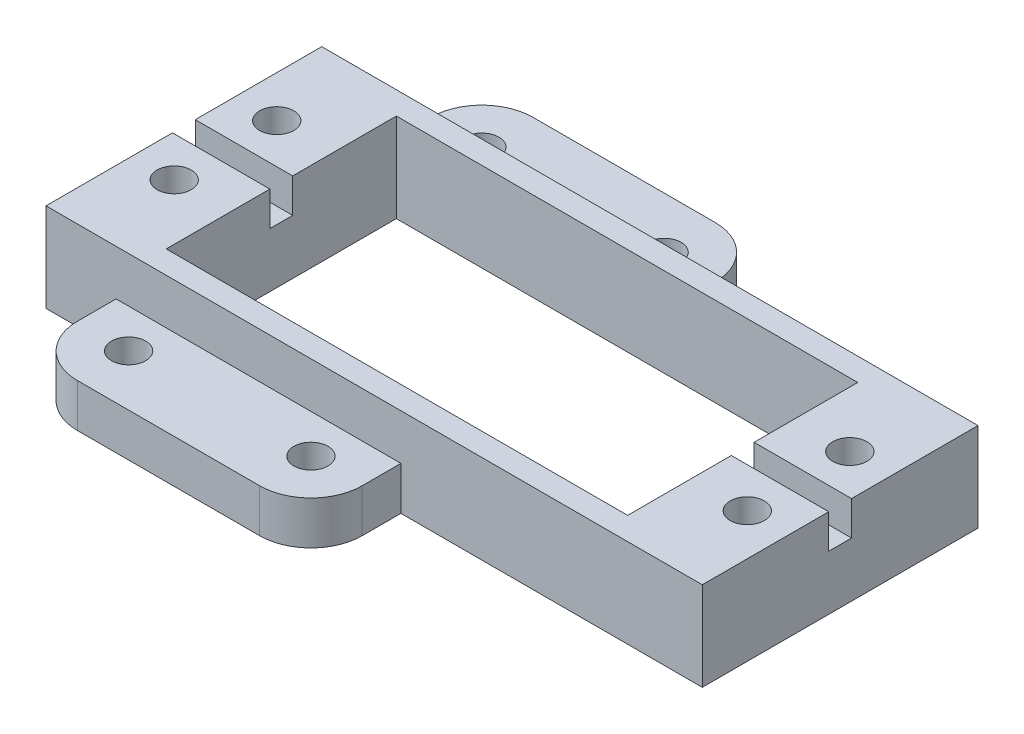
SolidWorks part; units mm, degrees
ref_plane "Front Plane" through (0, 0, 0) normal (0, 0, 1) x (1, 0, 0)
ref_plane "Top Plane" through (0, 0, 0) normal (0, 1, 0) x (1, 0, 0)
ref_plane "Right Plane" through (0, 0, 0) normal (1, 0, 0) x (0, 0, -1)
sketch "Sketch1" plane through (0, 0, 0) normal (0, 1, 0) x (1, 0, 0)
  line L0 (-101.8128, 12.4518) -> (-101.8128, 18.4813)
  line L1 (-101.8128, 21.4518) -> (-101.8128, 24.8665)
  line L2 (-94.5628, 5.4665) -> (-101.2128, 5.4665)
  line L3 (-95.1628, 6.0665) -> (-95.1628, 14.7945)
  line L4 (-54.8628, 14.7945) -> (-54.8628, 6.0665)
  line L5 (-48.2128, 18.4813) -> (-48.2128, 12.4518)
  line L6 (-85.1628, 25.4665) -> (-61.0205, 25.4665)
  line L7 (-95.2628, 25.4665) -> (-95.2628, 5.4665)
  line L8 (-101.8128, 25.4665) -> (-48.2128, 25.4665)
  line L9 (-101.8128, 25.4665) -> (-101.8128, 5.4665)
  line L10 (-101.8128, 5.4665) -> (-48.2128, 5.4665)
  line L11 (-48.2128, 25.4665) -> (-48.2128, 5.4665)
  line L12 (-95.1628, 25.4665) -> (-54.8628, 25.4665)
  line L13 (-95.1628, 25.4665) -> (-95.1628, 5.4665)
  line L14 (-95.1628, 5.4665) -> (-54.8628, 5.4665)
  line L15 (-54.8628, 25.4665) -> (-54.8628, 5.4665)
  line L17 (-54.7628, 25.4665) -> (-54.7628, 5.4665)
  line L19 (-95.2628, 25.5665) -> (-54.7628, 25.5665) construction
  line L20 (-95.2628, 5.3665) -> (-54.7628, 5.3665) construction
  line L22 (-95.2628, 25.5665) -> (-95.2628, 5.3665) construction
  line L23 (-54.7628, 25.5665) -> (-54.7628, 5.3665) construction
  circle A4 centre (-100.1628, 19.9665) radius 1.5
  circle A5 centre (-100.1628, 10.9665) radius 1.5
  circle A6 centre (-49.8628, 19.9665) radius 1.5
  circle A7 centre (-49.8628, 10.9665) radius 1.5
  dimension "D1" = 0.1
extrude "Boss-Extrude1" add sketch "Sketch1" along normal blind 7.8 contours L8 L17 L10 L11 L5 A7 A6 | L9 L10 L2 L7 L8 L1 L0 A5 A4
sketch "Sketch2" plane through (0, 7.8, 0) normal (0, 1, 0) x (1, 0, 0)
  line L5 (-101.8128, 25.4665) -> (-103.8128, 25.4665)
  line L6 (-101.8128, 25.4665) -> (-101.8128, 5.4665)
  line L7 (-101.8128, 5.4665) -> (-103.8128, 5.4665)
  line L8 (-101.8128, 25.4665) -> (-101.8128, 5.4665)
  line L9 (-101.8128, 5.4665) -> (-95.2628, 5.4665)
  line L10 (-95.2628, 5.4665) -> (-95.2628, 25.4665)
  line L11 (-95.2628, 25.4665) -> (-101.8128, 25.4665)
  line L12 (-101.8128, 25.4665) -> (-101.8128, 5.4665)
  line L13 (-101.8128, 5.4665) -> (-95.2628, 5.4665)
  line L14 (-95.2628, 5.4665) -> (-95.2628, 25.4665)
  line L15 (-95.2628, 25.4665) -> (-101.8128, 25.4665)
  line L16 (-103.8128, 25.4665) -> (-103.8128, 5.4665)
  line L17 (-48.2128, 25.4665) -> (-46.2128, 25.4665)
  line L18 (-48.2128, 25.4665) -> (-48.2128, 5.4665)
  line L19 (-48.2128, 5.4665) -> (-46.2128, 5.4665)
  line L20 (-46.2128, 25.4665) -> (-46.2128, 5.4665)
  line M11 (-48.2128, 5.4665) -> (-48.2128, 25.4665)
  dimension "D1" = 0
extrude "Boss-Extrude2" add sketch "Sketch2" against normal blind 7.8 contours L20 L17 L19 M11 | L5 L16 L7 L6
sketch "Sketch3" plane through (0, 7.8, 0) normal (0, 1, 0) x (1, 0, 0)
  line L0 (-54.7628, 25.4665) -> (-46.2128, 25.4665) construction
  line L1 (-95.2628, 25.4665) -> (-54.7628, 25.4665)
  line L2 (-95.2628, 25.4665) -> (-95.2628, 25.5665)
  line L3 (-95.2628, 25.5665) -> (-54.7628, 25.5665)
  line L4 (-54.7628, 25.4665) -> (-54.7628, 25.5665)
  line L5 (-95.2628, 5.4665) -> (-54.7628, 5.4665)
  line L6 (-95.2628, 5.4665) -> (-95.2628, 5.3665)
  line L7 (-95.2628, 5.3665) -> (-54.7628, 5.3665)
  line L8 (-54.7628, 5.4665) -> (-54.7628, 5.3665)
  line L9 (-103.8128, 25.4665) -> (-95.2628, 25.4665)
  line L10 (-103.8128, 25.4665) -> (-103.8128, 25.5665)
  line L11 (-103.8128, 25.5665) -> (-95.2628, 25.5665)
  line L12 (-95.2628, 25.4665) -> (-95.2628, 25.5665)
  line L13 (-54.7628, 25.5665) -> (-46.2128, 25.5665)
  line L14 (-54.7628, 25.5665) -> (-54.7628, 25.4665)
  line L15 (-54.7628, 25.4665) -> (-46.2128, 25.4665)
  line L16 (-46.2128, 25.5665) -> (-46.2128, 25.4665)
  line L17 (-103.8128, 5.4665) -> (-95.2628, 5.4665) construction
  line L18 (-103.8128, 5.4665) -> (-46.2128, 5.4665)
  line L19 (-103.8128, 5.4665) -> (-103.8128, 5.3665)
  line L20 (-103.8128, 5.3665) -> (-46.2128, 5.3665)
  line L21 (-46.2128, 5.4665) -> (-46.2128, 5.3665)
  line L22 (-103.8128, 25.4665) -> (-103.8128, 5.4665) construction
  line M5 (-95.2628, 25.4665) -> (-103.8128, 25.4665)
  line M7 (-103.8128, 5.4665) -> (-95.2628, 5.4665)
extrude "Boss-Extrude3" add sketch "Sketch3" against normal blind 7.8 contours L19 L20 L6 M7 | L11 L10 L2 M5 | L16 L13 L4 L15 | L21 L18 L8 L20
sketch "Sketch4" plane through (0, 7.8, 0) normal (0, 1, 0) x (1, 0, 0)
  line L1 (-103.8128, 25.5665) -> (-46.2128, 25.5665)
  line L2 (-103.8128, 25.5665) -> (-103.8128, 27.5665)
  line L3 (-103.8128, 27.5665) -> (-46.2128, 27.5665)
  line L4 (-46.2128, 25.5665) -> (-46.2128, 27.5665)
  line L5 (-103.8128, 5.3665) -> (-46.2128, 5.3665)
  line L6 (-103.8128, 5.3665) -> (-103.8128, 3.3665)
  line L7 (-103.8128, 3.3665) -> (-46.2128, 3.3665)
  line L8 (-46.2128, 5.3665) -> (-46.2128, 3.3665)
extrude "Boss-Extrude4" add sketch "Sketch4" against normal blind 7.8
sketch "Sketch5" plane through (0, 7.8, 0) normal (0, 1, 0) x (1, 0, 0)
  line L0 (-95.2628, 14.4665) -> (-103.8128, 16.4665) construction
  line L1 (-95.2628, 16.4665) -> (-103.8128, 14.4665) construction
  line L3 (-46.2128, 27.5665) -> (-46.2128, 3.3665) construction
  line L4 (-75.0128, 15.4665) -> (-75.0128, 20.7139)
  line L5 (-54.7628, 16.4665) -> (-46.2128, 16.4665)
  line L6 (-54.7628, 16.4665) -> (-54.7628, 14.4665)
  line L7 (-54.7628, 14.4665) -> (-46.2128, 14.4665)
  line L8 (-46.2128, 16.4665) -> (-46.2128, 14.4665)
  line L9 (-54.7628, 16.4665) -> (-46.2128, 14.4665) construction
  line L10 (-54.7628, 14.4665) -> (-46.2128, 16.4665) construction
  line L11 (-103.8128, 16.4665) -> (-103.8128, 14.4665)
  line L12 (-95.2628, 14.4665) -> (-103.8128, 14.4665)
  line L13 (-95.2628, 16.4665) -> (-95.2628, 14.4665)
  line L14 (-95.2628, 16.4665) -> (-103.8128, 16.4665)
  point P6 (-99.5378, 15.4665)
  point P10 (-50.4878, 15.4665)
  line M4 (-46.2128, 3.3665) -> (-46.2128, 27.5665)
  line M6 (-103.8128, 27.5665) -> (-103.8128, 3.3665)
  line M9 (-54.7628, 25.5665) -> (-54.7628, 5.3665)
  line M11 (-95.2628, 5.3665) -> (-95.2628, 25.5665)
extrude "Cut-Extrude1" cut sketch "Sketch5" against normal blind 3 contours L14 L12 M11 M6 | L7 L5 M9 M4
sketch "Sketch6" plane through (0, 7.8, 0) normal (0, 1, 0) x (1, 0, 0)
  line L0 (-82.1628, 15.4665) -> (-88.1628, 15.4665)
  line L1 (-95.2628, 15.4665) -> (-85.1628, 15.4665)
  line L2 (-95.2628, 14.4665) -> (-95.2628, 16.4665) construction
  line L3 (-97.661, -0.0334) -> (-97.661, 30.9666)
  line L4 (-72.661, -0.0334) -> (-72.661, 30.9666)
  line L5 (-93.161, -4.5334) -> (-77.161, -4.5334)
  line L6 (-93.161, 35.4666) -> (-77.161, 35.4666)
  line L7 (-103.8128, 16.4665) -> (-95.2628, 16.4665) construction
  line L8 (-95.2628, 16.4665) -> (-95.2628, 25.5665) construction
  line L9 (-95.2628, 25.5665) -> (-54.7628, 25.5665) construction
  line L10 (-54.7628, 25.5665) -> (-54.7628, 16.4665) construction
  line L11 (-54.7628, 16.4665) -> (-46.2128, 16.4665) construction
  line L12 (-46.2128, 16.4665) -> (-46.2128, 27.5665) construction
  line L13 (-46.2128, 27.5665) -> (-103.8128, 27.5665) construction
  line L14 (-103.8128, 27.5665) -> (-103.8128, 16.4665) construction
  line L15 (-95.2628, 5.3665) -> (-95.2628, 14.4665) construction
  line L16 (-95.2628, 14.4665) -> (-103.8128, 14.4665) construction
  line L17 (-103.8128, 14.4665) -> (-103.8128, 3.3665) construction
  line L18 (-103.8128, 3.3665) -> (-46.2128, 3.3665) construction
  line L19 (-46.2128, 3.3665) -> (-46.2128, 14.4665) construction
  line L20 (-46.2128, 14.4665) -> (-54.7628, 14.4665) construction
  line L21 (-54.7628, 14.4665) -> (-54.7628, 5.3665) construction
  line L22 (-54.7628, 5.3665) -> (-95.2628, 5.3665) construction
  line L23 (-103.8128, 16.4665) -> (-95.2628, 16.4665)
  line L24 (-95.2628, 16.4665) -> (-95.2628, 25.5665)
  line L25 (-95.2628, 25.5665) -> (-54.7628, 25.5665)
  line L26 (-54.7628, 25.5665) -> (-54.7628, 16.4665)
  line L27 (-54.7628, 16.4665) -> (-46.2128, 16.4665)
  line L28 (-46.2128, 16.4665) -> (-46.2128, 27.5665)
  line L29 (-46.2128, 27.5665) -> (-103.8128, 27.5665)
  line L30 (-103.8128, 27.5665) -> (-103.8128, 16.4665)
  line L31 (-95.2628, 5.3665) -> (-95.2628, 14.4665)
  line L32 (-95.2628, 14.4665) -> (-103.8128, 14.4665)
  line L33 (-103.8128, 14.4665) -> (-103.8128, 3.3665)
  line L34 (-103.8128, 3.3665) -> (-46.2128, 3.3665)
  line L35 (-46.2128, 3.3665) -> (-46.2128, 14.4665)
  line L36 (-46.2128, 14.4665) -> (-54.7628, 14.4665)
  line L37 (-54.7628, 14.4665) -> (-54.7628, 5.3665)
  line L38 (-54.7628, 5.3665) -> (-95.2628, 5.3665)
  circle A0 centre (-77.161, 30.9666) radius 1.5
  circle A1 centre (-93.161, 30.9666) radius 1.5
  circle A2 centre (-77.161, -0.0334) radius 1.5
  circle A3 centre (-93.161, -0.0334) radius 1.5
  circle A4 centre (-85.1628, 15.4665) radius 3
  circle A5 centre (-77.161, -0.0334) radius 4.5
  circle A6 centre (-93.161, -0.0334) radius 4.5
  circle A7 centre (-93.161, 30.9666) radius 4.5
  circle A8 centre (-77.161, 30.9666) radius 4.5
  line M9 (-46.2128, 27.5665) -> (-103.8128, 27.5665)
  dimension "D1" = 3
extrude "Boss-Extrude5" add sketch "Sketch6" against normal up to surface (7.8 mm away) contours A6 L34 L3 | A6 L34 A3 | A6 L5 A5 L34 | A5 L34 A2 | A5 L4 L34 | L29 A8 A0 | A8 L4 M9 | A8 L6 A7 M9 | L29 A7 A1 | A7 L3 M9 up to face at (-75.0128, 0, -15.4665)
sketch "Sketch7" plane through (0, 7.8, 0) normal (0, 1, 0) x (1, 0, 0)
  line L1 (-97.661, 27.5665) -> (-72.661, 27.5665)
  line L2 (-97.661, 27.5665) -> (-97.661, 3.3665)
  line L3 (-97.661, 3.3665) -> (-72.661, 3.3665)
  line L4 (-72.661, 27.5665) -> (-72.661, 3.3665)
  line L28 (-103.8128, 16.4665) -> (-95.2628, 16.4665)
  line L29 (-95.2628, 16.4665) -> (-95.2628, 25.5665)
  line L30 (-95.2628, 25.5665) -> (-54.7628, 25.5665)
  line L31 (-54.7628, 25.5665) -> (-54.7628, 16.4665)
  line L32 (-54.7628, 16.4665) -> (-46.2128, 16.4665)
  line L33 (-46.2128, 16.4665) -> (-46.2128, 27.5665)
  line L34 (-46.2128, 27.5665) -> (-72.661, 27.5665)
  line L35 (-72.661, 27.5665) -> (-72.661, 30.9666)
  line L36 (-77.161, 35.4666) -> (-93.161, 35.4666)
  line L37 (-97.661, 30.9666) -> (-97.661, 27.5665)
  line L38 (-97.661, 27.5665) -> (-103.8128, 27.5665)
  line L39 (-103.8128, 27.5665) -> (-103.8128, 16.4665)
  line L40 (-103.8128, 16.4665) -> (-95.2628, 16.4665)
  line L41 (-95.2628, 16.4665) -> (-95.2628, 25.5665)
  line L42 (-95.2628, 25.5665) -> (-54.7628, 25.5665)
  line L43 (-54.7628, 25.5665) -> (-54.7628, 16.4665)
  line L44 (-54.7628, 16.4665) -> (-46.2128, 16.4665)
  line L45 (-46.2128, 16.4665) -> (-46.2128, 27.5665)
  line L46 (-46.2128, 27.5665) -> (-72.661, 27.5665)
  line L47 (-72.661, 27.5665) -> (-72.661, 30.9666)
  line L48 (-77.161, 35.4666) -> (-93.161, 35.4666)
  line L49 (-97.661, 30.9666) -> (-97.661, 27.5665)
  line L50 (-97.661, 27.5665) -> (-103.8128, 27.5665)
  line L51 (-103.8128, 27.5665) -> (-103.8128, 16.4665)
  line L52 (-95.2628, 5.3665) -> (-95.2628, 14.4665)
  line L53 (-95.2628, 14.4665) -> (-103.8128, 14.4665)
  line L54 (-103.8128, 14.4665) -> (-103.8128, 3.3665)
  line L55 (-103.8128, 3.3665) -> (-97.661, 3.3665)
  line L56 (-97.661, 3.3665) -> (-97.661, -0.0334)
  line L57 (-93.161, -4.5334) -> (-77.161, -4.5334)
  line L58 (-72.661, -0.0334) -> (-72.661, 3.3665)
  line L59 (-72.661, 3.3665) -> (-46.2128, 3.3665)
  line L60 (-46.2128, 3.3665) -> (-46.2128, 14.4665)
  line L61 (-46.2128, 14.4665) -> (-54.7628, 14.4665)
  line L62 (-54.7628, 14.4665) -> (-54.7628, 5.3665)
  line L63 (-54.7628, 5.3665) -> (-95.2628, 5.3665)
  line L64 (-95.2628, 5.3665) -> (-95.2628, 14.4665)
  line L65 (-95.2628, 14.4665) -> (-103.8128, 14.4665)
  line L66 (-103.8128, 14.4665) -> (-103.8128, 3.3665)
  line L67 (-103.8128, 3.3665) -> (-97.661, 3.3665)
  line L68 (-97.661, 3.3665) -> (-97.661, -0.0334)
  line L69 (-93.161, -4.5334) -> (-77.161, -4.5334)
  line L70 (-72.661, -0.0334) -> (-72.661, 3.3665)
  line L71 (-72.661, 3.3665) -> (-46.2128, 3.3665)
  line L72 (-46.2128, 3.3665) -> (-46.2128, 14.4665)
  line L73 (-46.2128, 14.4665) -> (-54.7628, 14.4665)
  line L74 (-54.7628, 14.4665) -> (-54.7628, 5.3665)
  line L75 (-54.7628, 5.3665) -> (-95.2628, 5.3665)
  arc A4 (-72.661, 30.9666) -> (-77.161, 35.4666) centre (-77.161, 30.9666) ccw
  arc A5 (-93.161, 35.4666) -> (-97.661, 30.9666) centre (-93.161, 30.9666) ccw
  arc A6 (-72.661, 30.9666) -> (-77.161, 35.4666) centre (-77.161, 30.9666) ccw
  arc A7 (-93.161, 35.4666) -> (-97.661, 30.9666) centre (-93.161, 30.9666) ccw
  arc A8 (-97.661, -0.0334) -> (-93.161, -4.5334) centre (-93.161, -0.0334) ccw
  arc A9 (-77.161, -4.5334) -> (-72.661, -0.0334) centre (-77.161, -0.0334) ccw
  arc A10 (-97.661, -0.0334) -> (-93.161, -4.5334) centre (-93.161, -0.0334) ccw
  arc A11 (-77.161, -4.5334) -> (-72.661, -0.0334) centre (-77.161, -0.0334) ccw
  line M35 (-97.661, 3.3665) -> (-97.661, -0.0334)
  arc M36 (-97.661, -0.0334) -> (-93.161, -4.5334) centre (-93.161, -0.0334) ccw
  line M37 (-93.161, -4.5334) -> (-77.161, -4.5334)
  arc M38 (-77.161, -4.5334) -> (-72.661, -0.0334) centre (-77.161, -0.0334) ccw
  line M39 (-72.661, -0.0334) -> (-72.661, 3.3665)
  circle M45 centre (-93.161, -0.0334) radius 1.5
  circle M46 centre (-77.161, -0.0334) radius 1.5
  dimension "D1" = 0
  dimension "D2" = 0
extrude "Cut-Extrude2" cut sketch "Sketch7" against normal blind 4 contours L3 M35 M36 M37 M38 M39 M46 M45 | L48 A7 L49 L1 L47 A6
